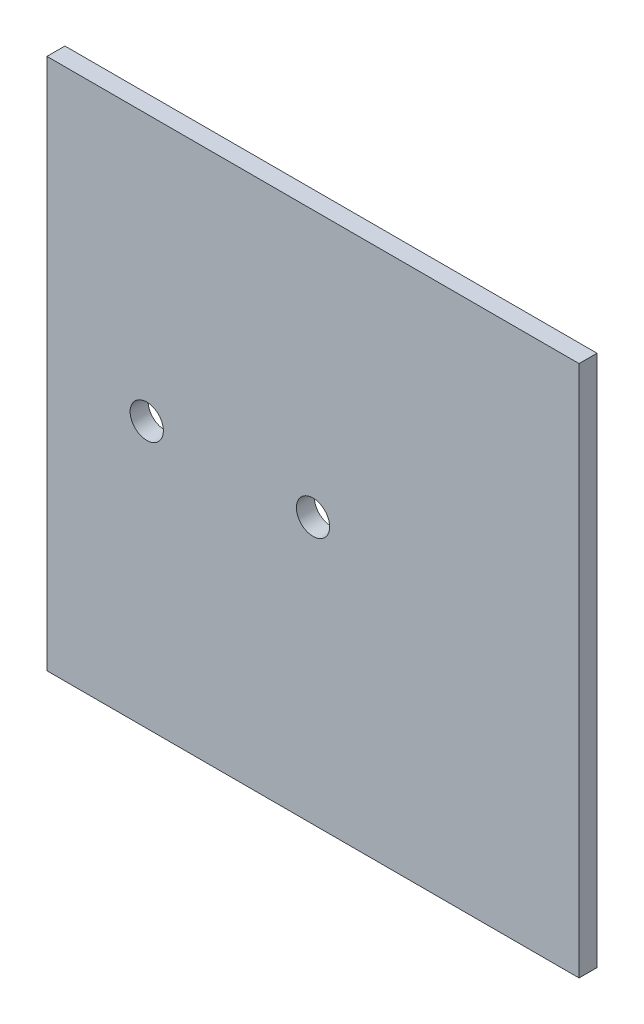
SolidWorks part; units mm, degrees
material "Acrílico (Impacto medio-alto)"
ref_plane "Alzado" through (0, 0, 0) normal (0, 0, 1) x (1, 0, 0)
ref_plane "Planta" through (0, 0, 0) normal (0, 1, 0) x (1, 0, 0)
ref_plane "Vista lateral" through (0, 0, 0) normal (1, 0, 0) x (0, 0, -1)
sketch "Croquis1" plane through (0, 0, 0) normal (0, 0, 1) x (1, 0, 0)
  line L1 (-82.7, 40) -> (-2.7, 40)
  line L2 (-82.7, 40) -> (-82.7, -40)
  line L3 (-82.7, -40) -> (-2.7, -40)
  line L4 (-2.7, 40) -> (-2.7, -40)
extrude "Saliente-Extruir2" add sketch "Croquis1" against normal blind 2.7
sketch "Croquis2" plane through (0, 0, -2.7) normal (0, 0, -1) x (-1, 0, 0)
  line L0 (42.7, 40) -> (42.7, -40) construction
  line L1 (2.7, 40) -> (82.7, 40) construction
  line L2 (82.7, -40) -> (2.7, -40) construction
  line L3 (42.7, 0) -> (82.7, 0) construction
  line L4 (82.7, 40) -> (82.7, -40) construction
  circle A0 centre (67.7, 0) radius 2.5
  circle A1 centre (42.7, 0) radius 2.5
  dimension "D1" = 5
  dimension "D2" = 15
  dimension "D3" = 40
extrude "Cortar-Extruir1" cut sketch "Croquis2" against normal blind 2.7
